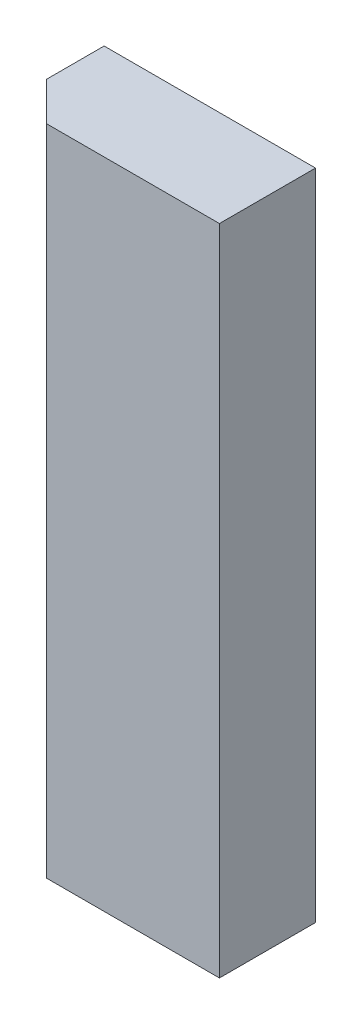
SolidWorks part; units mm, degrees
ref_plane "Front Plane" through (0, 0, 0) normal (1, 0, 0) x (0, 1, 0)
ref_plane "Top Plane" through (0, 0, 0) normal (0, 0, 1) x (0, 1, 0)
ref_plane "Right Plane" through (0, 0, 0) normal (0, 1, 0) x (-1, 0, 0)
sketch "Sketch1" plane through (0, 0, 0) normal (0, 0, 1) x (0, 1, 0)
  line L1 (0, 0) -> (170, 0)
  line L2 (0, 0) -> (0, 55)
  line L3 (0, 55) -> (170, 55)
  line L4 (170, 0) -> (170, 55)
  dimension "D1" = 170
  dimension "D2" = 55
extrude "Boss-Extrude1" add sketch "Sketch1" along normal blind 25
chamfer "Chamfer1" distance 10 angle 45 1 edges at (-55, 85, 25)
